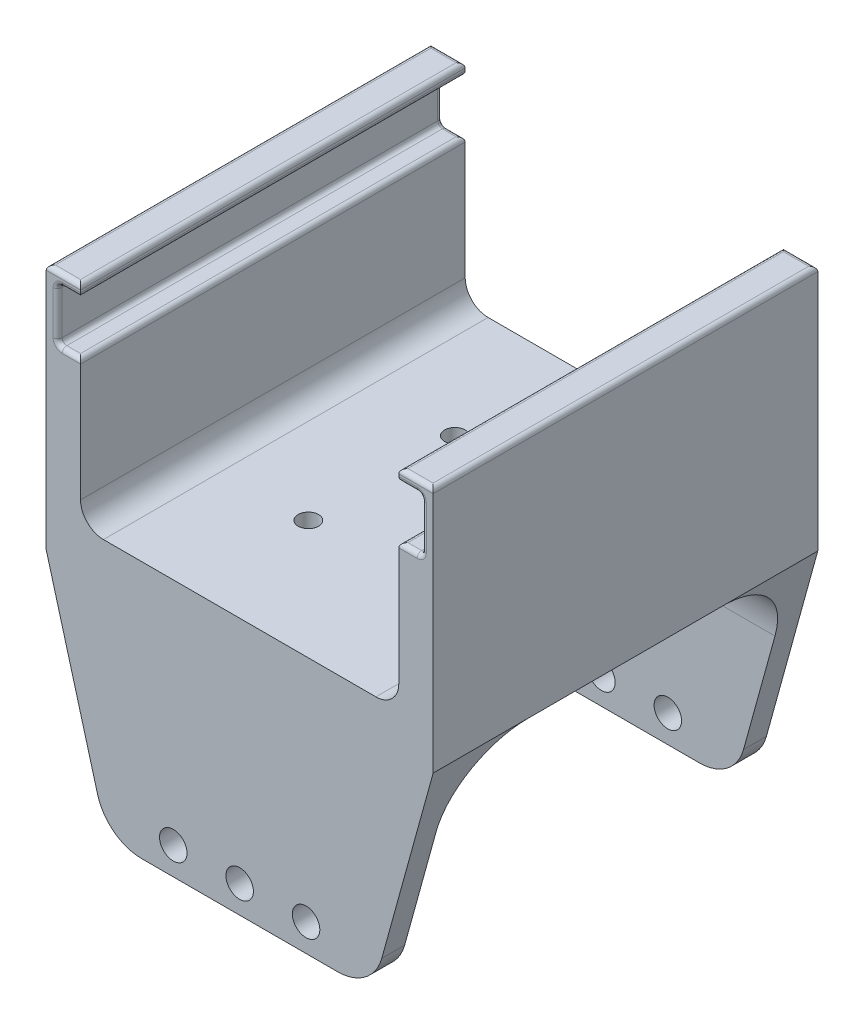
SolidWorks part; units mm, degrees
ref_plane "Front Plane" through (0, 0, 0) normal (0, 0, 1) x (1, 0, 0)
ref_plane "Top Plane" through (0, 0, 0) normal (0, 1, 0) x (1, 0, 0)
ref_plane "Right Plane" through (0, 0, 0) normal (1, 0, 0) x (0, 0, -1)
sketch "Sketch4" plane through (0, 25, 0) normal (0, 1, 0) x (1, 0, 0)
  line L0 (-19, 81) -> (39, -7) construction
  line L2 (52.25, -5) -> (-32.25, -5)
  line L3 (52.25, -5) -> (52.25, 79)
  line L4 (52.25, 79) -> (-32.25, 79)
  line L5 (-32.25, -5) -> (-32.25, 79)
  line L6 (10, 79) -> (10, -5) construction
  line L7 (52.25, 37) -> (-32.25, 37) construction
  point P4 (10, 37)
  dimension "D1" = 84
  dimension "D2" = 84.5
extrude "Boss-Extrude1" add sketch "Sketch4" along normal blind 8.175
sketch "Sketch5" plane through (0, 25, 0) normal (0, -1, 0) x (1, 0, 0)
  line L0 (52.25, 5) -> (52.25, -79) construction
  line L1 (-32.25, 5) -> (52.25, 5)
  line L2 (-32.25, 5) -> (-32.25, 0)
  line L3 (-32.25, 0) -> (52.25, 0)
  line L4 (52.25, 5) -> (52.25, 0)
  line L6 (-32.25, -79) -> (52.25, -79)
  line L7 (-32.25, -79) -> (-32.25, -74)
  line L8 (-32.25, -74) -> (52.25, -74)
  line L9 (52.25, -79) -> (52.25, -74)
  dimension "D1" = 5
extrude "Boss-Extrude2" add sketch "Sketch5" along normal blind 48
sketch "Sketch6" plane through (0, 25, 0) normal (0, -1, 0) x (1, 0, 0)
  circle A0 centre (-1, -21) radius 2.225
  circle A1 centre (-1, -53) radius 2.225
extrude "Cut-Extrude1" cut sketch "Sketch6" against normal blind 48
sketch "Sketch7" plane through (0, 33.175, 0) normal (0, 1, 0) x (1, 0, 0)
  line L0 (-32.25, -5) -> (52.25, -5) construction
  line L1 (-32.25, 79) -> (-24.75, 79)
  line L2 (-32.25, 79) -> (-32.25, -5)
  line L3 (-32.25, -5) -> (-24.75, -5)
  line L4 (-24.75, 79) -> (-24.75, -5)
  line L6 (52.25, 79) -> (44.75, 79)
  line L7 (52.25, 79) -> (52.25, -5)
  line L8 (52.25, -5) -> (44.75, -5)
  line L9 (44.75, 79) -> (44.75, -5)
  dimension "D1" = 7.5
extrude "Boss-Extrude3" add sketch "Sketch7" along normal blind 31.675
sketch "Sketch8" plane through (0, 64.85, 0) normal (0, 1, 0) x (1, 0, 0)
  line L0 (-32.25, -5) -> (-24.75, -5) construction
  line L1 (-32.25, 79) -> (-29.75, 79)
  line L2 (-32.25, 79) -> (-32.25, -5)
  line L3 (-32.25, -5) -> (-29.75, -5)
  line L4 (-29.75, 79) -> (-29.75, -5)
  line L5 (52.25, 79) -> (44.75, 79) construction
  line L6 (52.25, -5) -> (49.75, -5)
  line L7 (52.25, -5) -> (52.25, 79)
  line L8 (52.25, 79) -> (49.75, 79)
  line L9 (49.75, -5) -> (49.75, 79)
  dimension "D1" = 2.5
extrude "Boss-Extrude4" add sketch "Sketch8" along normal blind 11.5
sketch "Sketch9" plane through (0, 0, 0) normal (0, 0, -1) x (-1, 0, 0)
  circle A0 centre (-10, -17) radius 3
  circle A1 centre (-24.5, -17) radius 3
  circle A2 centre (4.5, -17) radius 3
extrude "Cut-Extrude2" cut sketch "Sketch9" against normal blind 5 and the other way blind 93
sketch "Sketch10" plane through (0, 76.35, 0) normal (0, 1, 0) x (1, 0, 0)
  line L1 (52.25, 79) -> (44.75, 79)
  line L2 (52.25, 79) -> (52.25, -5)
  line L3 (52.25, -5) -> (44.75, -5)
  line L4 (44.75, 79) -> (44.75, -5)
  line L5 (-32.25, 79) -> (-24.75, 79)
  line L6 (-32.25, 79) -> (-32.25, -5)
  line L7 (-32.25, -5) -> (-24.75, -5)
  line L8 (-24.75, 79) -> (-24.75, -5)
extrude "Boss-Extrude5" add sketch "Sketch10" along normal blind 2.5
fillet "Fillet1" radius 1 28 edges at (-29.75, 70.6, -79) (-29.75, 70.6, 5) (49.75, 70.6, 5) (49.75, 70.6, -79) (48.5, 78.85, 5) (44.75, 78.85, -37) (48.5, 78.85, -79) (52.25, 78.85, -37) (-28.5, 78.85, -79) (-24.75, 78.85, -37) (-28.5, 78.85, 5) (-24.75, 64.85, -37) (-27.25, 64.85, 5) (-29.75, 64.85, -37) (-27.25, 64.85, -79) (-24.75, 76.35, -37) (-27.25, 76.35, -79) (-29.75, 76.35, -37) (-27.25, 76.35, 5) (47.25, 76.35, -79) (44.75, 76.35, -37) (47.25, 76.35, 5) (49.75, 76.35, -37) (47.25, 64.85, 5) (44.75, 64.85, -37) (47.25, 64.85, -79) (49.75, 64.85, -37) (-32.25, 78.85, -37)
sketch "Sketch11" plane through (0, 0, 0) normal (0, 0, -1) x (-1, 0, 0)
  line L3 (32.25, -23) -> (-52.25, -23) construction
  line L4 (19, -23) -> (32.25, -23)
  line L5 (32.25, -23) -> (32.25, 25)
  line L6 (32.25, 25) -> (19, -23)
  line L7 (-39, -23) -> (-52.25, -23)
  line L8 (-52.25, -23) -> (-52.25, 25)
  line L9 (-52.25, 25) -> (-39, -23)
  dimension "D1" = 13.25
  dimension "D2" = 13.25
extrude "Cut-Extrude3" cut sketch "Sketch11" against normal blind 24.5 and the other way blind 88
fillet "Fillet2" radius 10 4 edges at (39, -23, 2.5) (-19, -23, 2.5) (39, -23, -76.5) (-19, -23, -76.5)
fillet "Fillet3" radius 5 2 edges at (44.75, 33.175, -37) (-24.75, 33.175, -37)
fillet "Fillet4" radius 15.75 2 edges at (10, 25, 0) (10, 25, -74)
